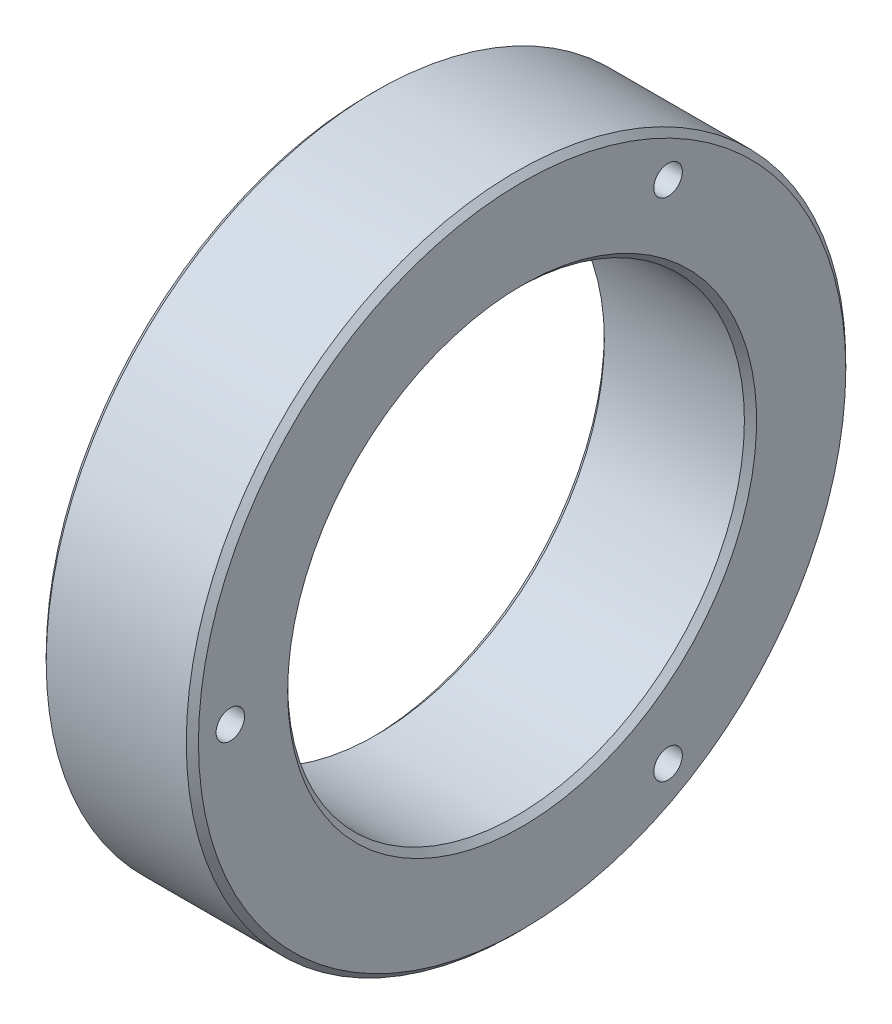
SolidWorks part; units mm, degrees
ref_plane "Front Plane" through (0, 0, 0) normal (1, 0, 0) x (0, 1, 0)
ref_plane "Top Plane" through (0, 0, 0) normal (0, 0, 1) x (0, 1, 0)
ref_plane "Right Plane" through (0, 0, 0) normal (0, 1, 0) x (-1, 0, 0)
sketch "Sketch1" plane through (0, 0, 0) normal (0, 0, 1) x (0, 1, 0)
  line L0 (82.5246, 0) -> (82.5246, -38.1)
  line L1 (82.5246, -38.1) -> (57.15, -38.1)
  line L2 (57.15, -38.1) -> (57.15, 0)
  line L3 (57.15, 0) -> (82.5246, 0)
  line L4 (0, 25.4) -> (0, -63.5) construction
revolve "Revolve1" add sketch "Sketch1" angle 360 about L4
sketch "Sketch2" plane through (0, 0, 0) normal (1, 0, 0) x (0, 1, 0)
  circle A0 centre (0, 73.025) radius 3.5687
extrude "Cut-Extrude2" cut sketch "Sketch2" along normal through all
sketch "Sketch3" plane through (0, 0, 0) normal (1, 0, 0) x (0, 1, 0)
  circle A0 centre (0, 73.025) radius 5.5626
extrude "Cut-Extrude4" cut sketch "Sketch3" along normal blind 9.652
sketch "Sketch4" plane through (0, 0, 0) normal (1, 0, 0) x (0, 1, 0)
  circle A0 centre (-63.246, -36.5252) radius 3.5687
extrude "Cut-Extrude6" cut sketch "Sketch4" along normal through all
sketch "Sketch5" plane through (0, 0, 0) normal (1, 0, 0) x (0, 1, 0)
  circle A0 centre (-63.246, -36.5252) radius 5.5626
extrude "Cut-Extrude8" cut sketch "Sketch5" along normal blind 9.652
sketch "Sketch6" plane through (0, 0, 0) normal (1, 0, 0) x (0, 1, 0)
  circle A0 centre (63.246, -36.5252) radius 3.5687
extrude "Cut-Extrude10" cut sketch "Sketch6" along normal through all
sketch "Sketch7" plane through (0, 0, 0) normal (1, 0, 0) x (0, 1, 0)
  circle A0 centre (63.246, -36.5252) radius 5.5626
extrude "Cut-Extrude12" cut sketch "Sketch7" along normal blind 9.652
sketch "Sketch8" plane through (0, 0, 0) normal (1, 0, 0) x (0, 1, 0)
  circle A0 centre (-69.85, 0) radius 3.9687
extrude "Cut-Extrude14" cut sketch "Sketch8" along normal blind 25.4
sketch "Sketch9" plane through (0, 0, 0) normal (1, 0, 0) x (0, 1, 0)
  circle A0 centre (69.85, 0) radius 3.9687
extrude "Cut-Extrude16" cut sketch "Sketch9" along normal blind 25.4
chamfer "Chamfer1" distance 1.524 angle 45 4 edges at (38.1, 0, 57.15) (0, 0, 57.15) (38.1, 0, 82.5246) (0, 0, 82.5246)
